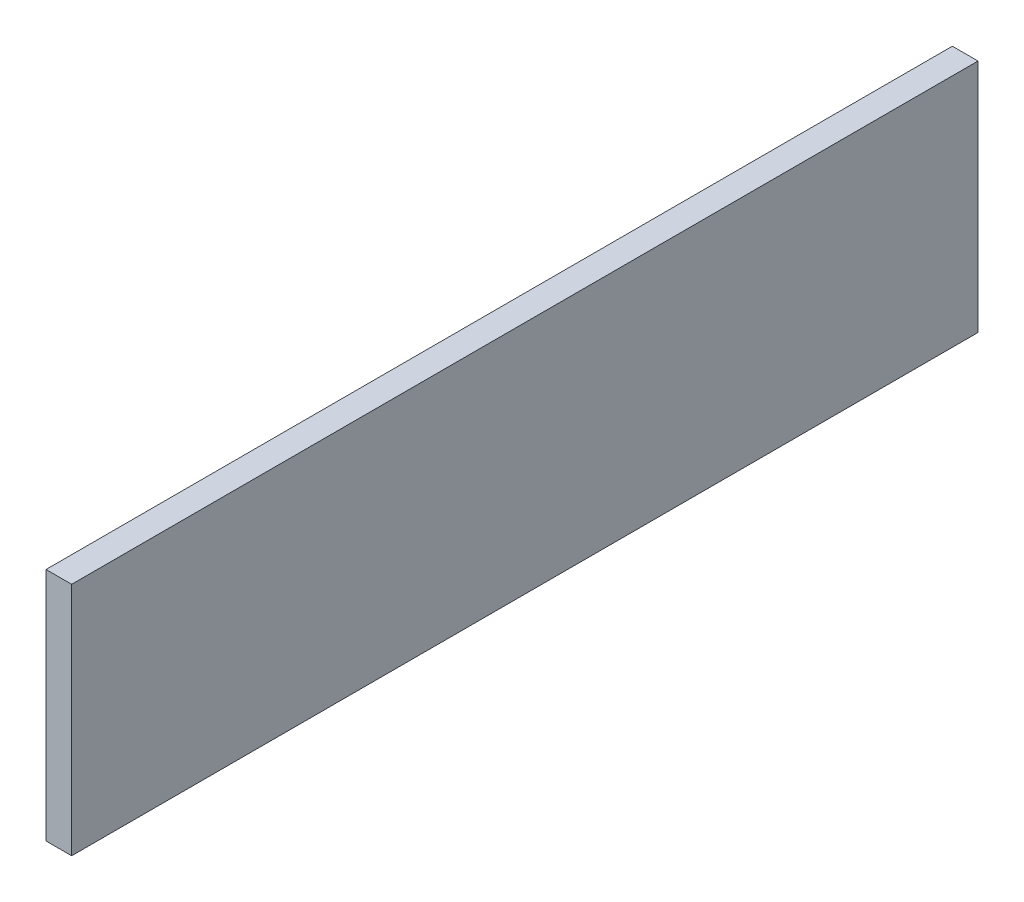
SolidWorks part; units mm, degrees
material "Q355"
ref_plane "前视基准面" through (0, 0, 0) normal (0, 0, 1) x (1, 0, 0)
ref_plane "上视基准面" through (0, 0, 0) normal (0, 1, 0) x (1, 0, 0)
ref_plane "右视基准面" through (0, 0, 0) normal (1, 0, 0) x (0, 0, -1)
sketch "草图1" plane through (0, 0, 0) normal (1, 0, 0) x (0, 0, -1)
  line L1 (-212, 55) -> (212, 55)
  line L2 (-212, 55) -> (-212, -55)
  line L3 (-212, -55) -> (212, -55)
  line L4 (212, 55) -> (212, -55)
  line L5 (-212, 55) -> (212, -55) construction
  line L6 (-212, -55) -> (212, 55) construction
  point P0 (0, 0)
  dimension "D1" = 424
  dimension "D2" = 110
extrude "凸台-拉伸1" add sketch "草图1" along normal blind 12
